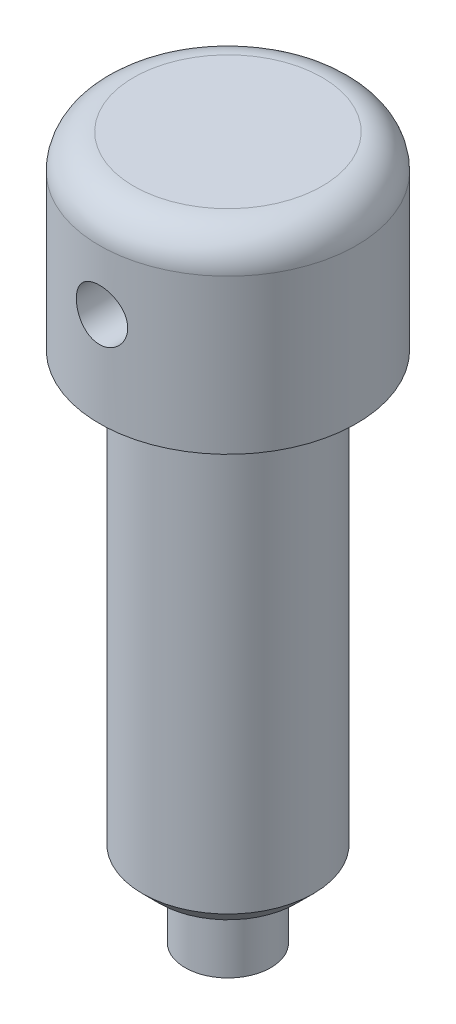
SolidWorks part; units mm, degrees
ref_plane "前基準面" through (0, 0, 0) normal (0, 0, 1) x (1, 0, 0)
ref_plane "上基準面" through (0, 0, 0) normal (0, 1, 0) x (1, 0, 0)
ref_plane "右基準面" through (0, 0, 0) normal (1, 0, 0) x (0, 0, -1)
sketch "草圖1" plane through (0, 0, 0) normal (1, 0, 0) x (0, 0, -1)
  line L0 (0, 0) -> (0, 41) construction
  line L1 (0, 41) -> (-7.5, 41)
  line L2 (-7.5, 41) -> (-7.5, 30)
  line L3 (-7.5, 30) -> (-5, 30)
  line L4 (-5, 30) -> (-5, 4)
  line L6 (-5, 4) -> (-2.5, 4)
  line L7 (-2.5, 4) -> (-2.5, 0)
  line L8 (-2.5, 0) -> (0, 0)
  line L9 (0, 0) -> (0, 41)
  dimension "D1" = 5
  dimension "D2" = 4
  dimension "D5" = 10
  dimension "D6" = 30
  dimension "D7" = 15
  dimension "D8" = 11
revolve "旋轉1" add sketch "草圖1" angle 360 about L0
cosmetic thread "裝飾螺紋線1" parameters "D2"=8.5
sketch "草圖2" plane through (0, 0, 0) normal (1, 0, 0) x (0, 0, -1)
  line L0 (-7.5, 35.5) -> (7.5, 35.5) construction
  line L1 (7.5, 30) -> (7.5, 41) construction
  line L2 (-7.5, 41) -> (-7.5, 30) construction
  line L3 (-7.5, 35.5) -> (-7.5, 37)
  line L4 (-7.5, 37) -> (7.5, 37)
  line L5 (7.5, 37) -> (7.5, 35.5)
  line L6 (-7.5, 35.5) -> (7.5, 35.5)
  dimension "D1" = 3
revolve "除料-旋轉1" cut sketch "草圖2" angle 360 about L0
fillet "圓角1" radius 2 1 edges at (0, 41, -7.5)
chamfer "導角1" distance 1 angle 45 1 edges at (0, 4, -5)
